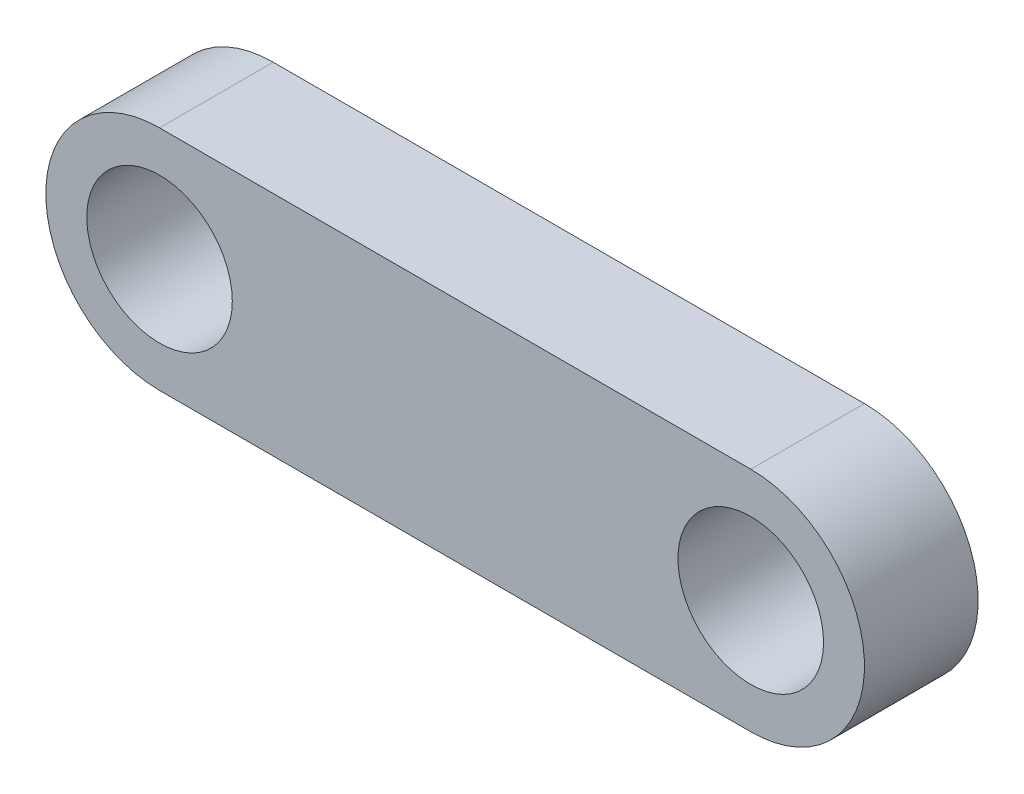
SolidWorks part; units mm, degrees
ref_plane "前视基准面" through (0, 0, 0) normal (0, 0, 1) x (1, 0, 0)
ref_plane "上视基准面" through (0, 0, 0) normal (0, 1, 0) x (1, 0, 0)
ref_plane "右视基准面" through (0, 0, 0) normal (1, 0, 0) x (0, 0, -1)
other "Configuration Table"
sketch "草图1" plane through (0, 0, 0) normal (0, 0, 1) x (1, 0, 0)
  line L0 (-4.7939, 0) -> (8.2061, 0) construction
  line L1 (-4.7939, 2) -> (8.2061, 2)
  line L2 (-4.7939, -2) -> (8.2061, -2)
  circle A0 centre (-4.7939, 0) radius 1.6
  circle A1 centre (8.2061, 0) radius 1.6
  arc A2 (-4.7939, 2) -> (-4.7939, -2) centre (-4.7939, 0) ccw
  arc A3 (8.2061, -2) -> (8.2061, 2) centre (8.2061, 0) ccw
  point P4 (1.7061, 0)
  dimension "D1" = 13
  dimension "D2" = 3.2
  dimension "D3" = 3.2
  dimension "D4" = 4.7939
  dimension "D5" = 8.2061
  dimension "D6" = 4
extrude "凸台-拉伸2" add sketch "草图1" along normal blind 2.5
sketch "草图2" plane through (0, 0, 0) normal (0, 0, -1) x (-1, 0, 0)
  line L0 (-8.2061, 0) -> (4.7939, 0) construction
  line L1 (-8.2061, 2.5) -> (4.7939, 2.5)
  line L2 (-8.2061, -2.5) -> (4.7939, -2.5)
  arc A0 (-8.2061, 2.5) -> (-8.2061, -2.5) centre (-8.2061, 0) ccw
  arc A1 (4.7939, -2.5) -> (4.7939, 2.5) centre (4.7939, 0) ccw
  circle A2 centre (4.7939, 0) radius 1.6 construction
  circle A3 centre (-8.2061, 0) radius 1.6 construction
  circle A4 centre (4.7939, 0) radius 1.6
  circle A5 centre (-8.2061, 0) radius 1.6
  point P4 (-1.7061, 0)
  dimension "D1" = 5
extrude "凸台-拉伸4" add sketch "草图2" against normal blind 2.5
